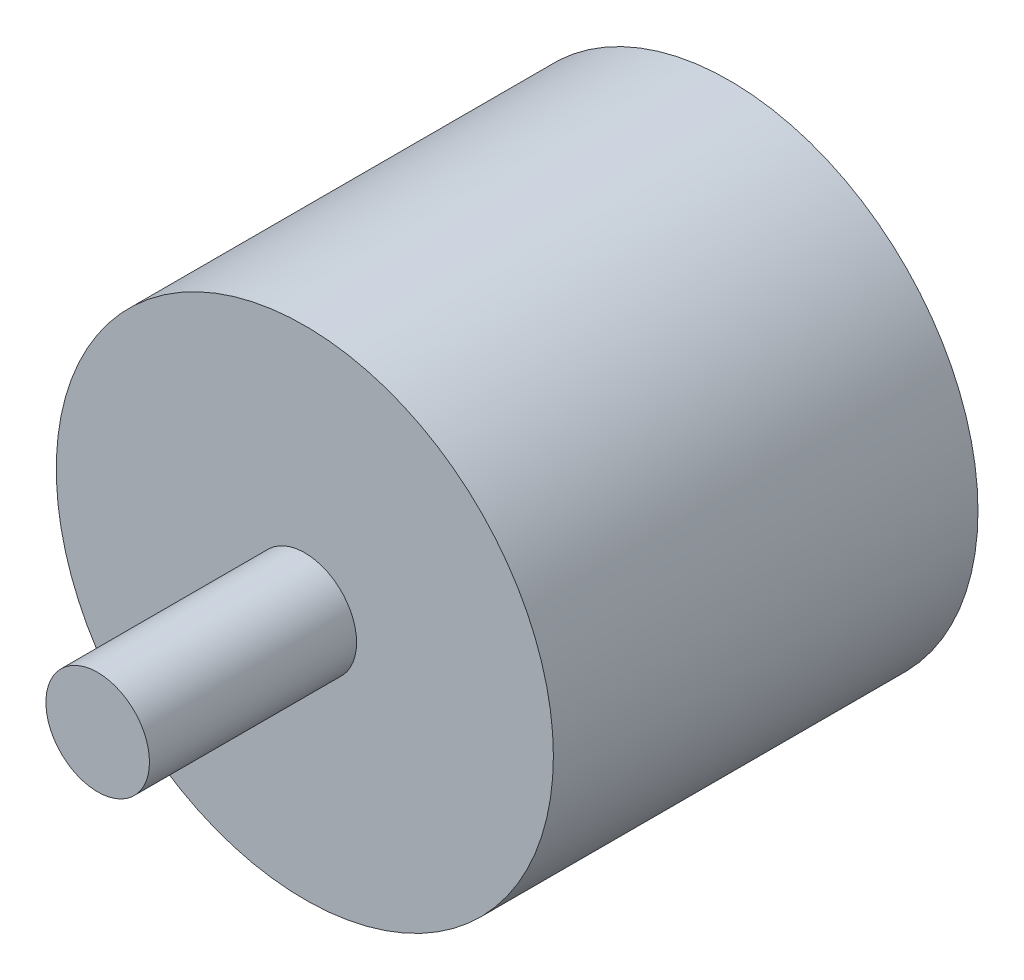
SolidWorks part; units mm, degrees
ref_plane "Plan de face" through (0, 0, 0) normal (0, 0, 1) x (1, 0, 0)
ref_plane "Plan de dessus" through (0, 0, 0) normal (0, 1, 0) x (1, 0, 0)
ref_plane "Plan de droite" through (0, 0, 0) normal (1, 0, 0) x (0, 0, -1)
sketch "Esquisse1" plane through (0, 0, 0) normal (0, 0, 1) x (1, 0, 0)
  circle A0 centre (0, 0) radius 12
  dimension "D1" = 24
extrude "Boss.-Extru.1" add sketch "Esquisse1" along normal blind 20.5
sketch "Esquisse2" plane through (0, 0, 20.5) normal (0, 0, 1) x (1, 0, 0)
  circle A0 centre (0, 0) radius 2.5
  dimension "D1" = 5
extrude "Boss.-Extru.2" add sketch "Esquisse2" along normal blind 10
